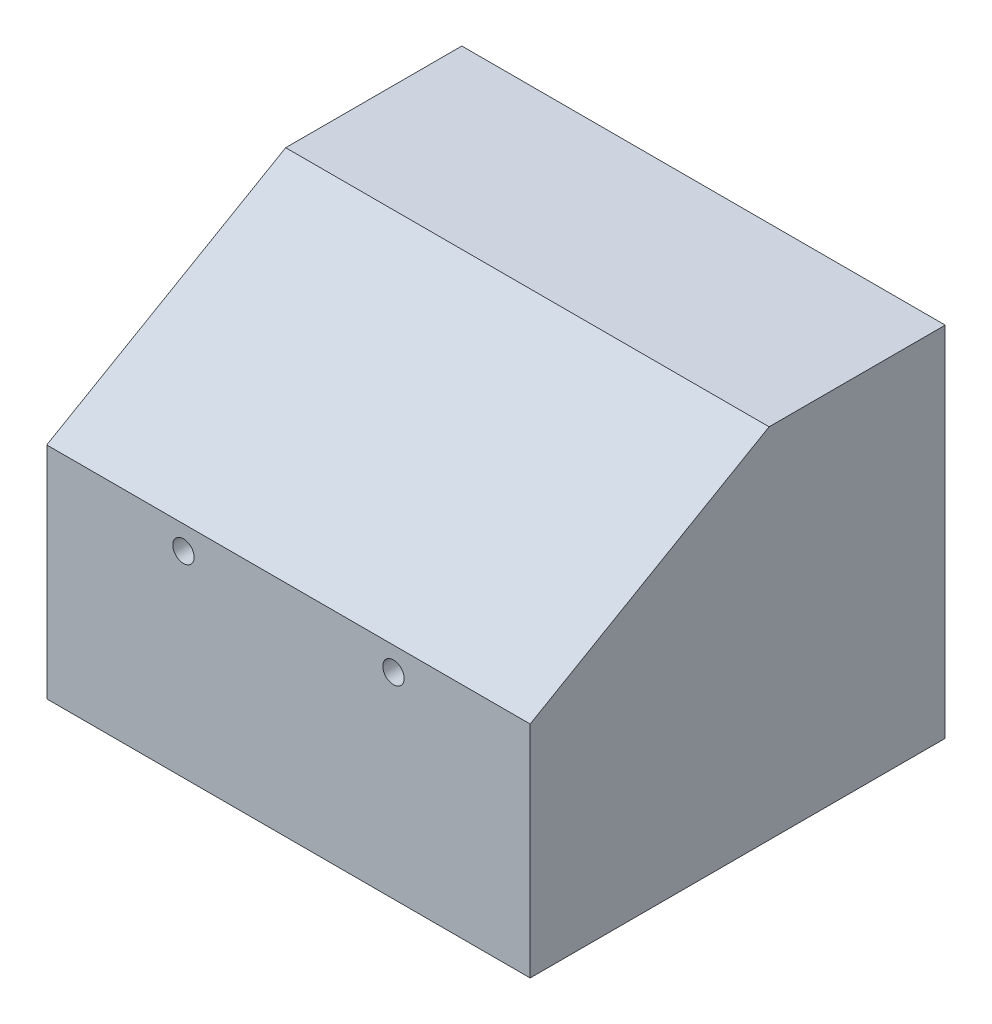
SolidWorks part; units mm, degrees
ref_plane "Ebene vorne" through (0, 0, 0) normal (0, 0, 1) x (1, 0, 0)
ref_plane "Ebene oben" through (0, 0, 0) normal (0, 1, 0) x (1, 0, 0)
ref_plane "Ebene rechts" through (0, 0, 0) normal (1, 0, 0) x (0, 0, -1)
sketch "Skizze2" plane through (0, 0, 0) normal (0, 0, 1) x (1, 0, 0)
  line L1 (97.25, -72) -> (-97.25, -72)
  line L2 (97.25, -72) -> (97.25, 72)
  line L3 (97.25, 72) -> (-97.25, 72)
  line L4 (-97.25, -72) -> (-97.25, 72)
  line L5 (97.25, -72) -> (-97.25, 72) construction
  line L6 (97.25, 72) -> (-97.25, -72) construction
  point P0 (0, 0)
  dimension "D1" = 144
  dimension "D2" = 194.5
extrude "Aufsatz-Linear austragen1" add sketch "Skizze2" along normal blind 167
ref_plane "Ebene1" through (0, 0, 0) normal (0, 1, 0) x (1, 0, 0)
ref_plane "Ebene2" through (0, 0, 0) normal (1, 0, 0) x (0, -1, 0)
sketch "Skizze3" plane through (0, 0, 167) normal (0, 0, 1) x (1, 0, 0)
  line L0 (97.25, 72) -> (-97.25, 72) construction
  line L1 (-97.25, 72) -> (-97.25, -72) construction
  circle A0 centre (-42.25, 7) radius 26.856
  dimension "D1" = 65
  dimension "D2" = 55
hole_wizard "Stirnsenkung für M4 Senkschraube (Kopf Button)1" positions "Skizze5" profile "Skizze4" counterbore size "M4" standard "ANSI Metrisch" end condition through all
sketch "Skizze5" plane through (0, 0, 167) normal (0, 0, 1) x (1, 0, 0)
  point P0 (-42.25, 7)
sketch "Skizze4" plane through (-42.25, 7, 167) normal (1, 0, 0) x (0, -1, 0)
  line L0 (0, 0) -> (0, 167)
  line L1 (0, 167) -> (2.25, 167)
  line L3 (2.25, 167) -> (2.25, 162)
  line L4 (2.25, 162) -> (4.3, 162)
  line L5 (4.3, 162) -> (4.3, 0)
  line L7 (4.3, 0) -> (0, 0)
  line L11 (0, -6.35) -> (0, 107.95) construction
  dimension "Bohrerdurchmesser" = 4.5
  dimension "Bohrungstiefe" = 167
  dimension "Senkdurchmesser2" = 8.6
  dimension "Senktiefe2" = 162
mirror "Spiegeln1" about plane through (0, 0, 0) normal (1, 0, 0) of "Stirnsenkung für M4 Senkschraube (Kopf Button)1"
sketch "Skizze6" plane through (-97.25, 0, 0) normal (-1, 0, 0) x (0, 0, 1)
  line L0 (70.8712, 72) -> (167, 16.5)
  line L1 (167, 72) -> (0, 72) construction
  line L2 (167, 72) -> (167, -72) construction
  line L3 (70.8712, 72) -> (82.5938, 116.8193)
  line L4 (82.5938, 116.8193) -> (205.1881, 84.7543)
  line L5 (205.1881, 84.7543) -> (167, 16.5)
  dimension "D1" = 111
  dimension "D2" = 30
extrude "Schnitt-Linear austragen1" cut sketch "Skizze6" against normal through all
